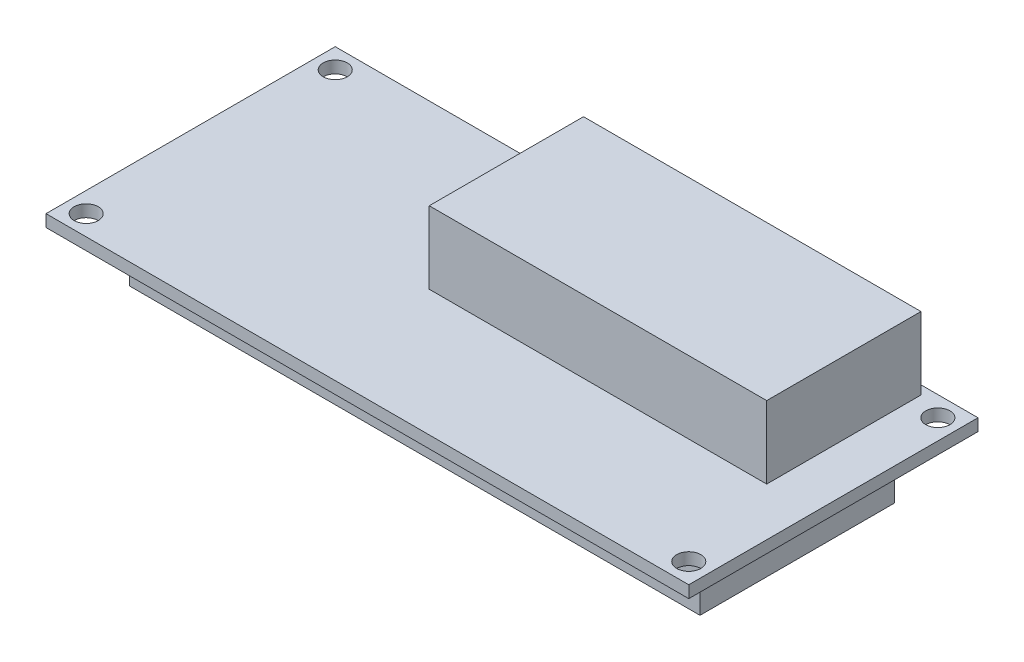
SolidWorks part; units mm, degrees
ref_plane "Спереди" through (0, 0, 0) normal (0, 0, 1) x (1, 0, 0)
ref_plane "Сверху" through (0, 0, 0) normal (0, 1, 0) x (1, 0, 0)
ref_plane "Справа" through (0, 0, 0) normal (1, 0, 0) x (0, 0, -1)
sketch "Эскиз1" plane through (0, 0, 0) normal (0, 1, 0) x (1, 0, 0)
  line L1 (-23.6364, 10.5455) -> (56.3636, 10.5455)
  line L2 (-23.6364, 10.5455) -> (-23.6364, -25.4545)
  line L3 (-23.6364, -25.4545) -> (56.3636, -25.4545)
  line L4 (56.3636, 10.5455) -> (56.3636, -25.4545)
  circle A0 centre (-21.1364, -22.9545) radius 1.5
  circle A1 centre (53.8636, 8.0455) radius 1.5
  circle A2 centre (-21.1364, 8.0455) radius 1.5
  circle A3 centre (53.8636, -22.9545) radius 1.5
  dimension "D1" = 80
  dimension "D2" = 36
  dimension "D3" = 2.5
  dimension "D4" = 2.5
  dimension "D5" = 2.5
  dimension "D6" = 2.5
  dimension "D7" = 2.5
  dimension "D8" = 2.5
  dimension "D9" = 2.5
  dimension "D10" = 2.5
extrude "Бобышка-Вытянуть1" add sketch "Эскиз1" along normal blind 1.5
sketch "Эскиз2" plane through (0, 0, 0) normal (0, -1, 0) x (1, 0, 0)
  line L0 (-23.6364, -10.5455) -> (-23.6364, 25.4545) construction
  line L1 (-19.1364, 19.5545) -> (51.8636, 19.5545)
  line L2 (-19.1364, 19.5545) -> (-19.1364, -4.6455)
  line L3 (-19.1364, -4.6455) -> (51.8636, -4.6455)
  line L4 (51.8636, 19.5545) -> (51.8636, -4.6455)
  line L5 (-23.6364, 25.4545) -> (56.3636, 25.4545) construction
  dimension "D1" = 71
  dimension "D2" = 24.2
  dimension "D3" = 4.5
  dimension "D4" = 5.9
extrude "Бобышка-Вытянуть2" add sketch "Эскиз2" along normal blind 7
sketch "Эскиз3" plane through (0, 1.5, 0) normal (0, 1, 0) x (1, 0, 0)
  line L0 (56.3636, -25.4545) -> (56.3636, 10.5455) construction
  line L1 (8.3636, 9.4455) -> (50.3636, 9.4455)
  line L2 (8.3636, 9.4455) -> (8.3636, -9.7545)
  line L3 (8.3636, -9.7545) -> (50.3636, -9.7545)
  line L4 (50.3636, 9.4455) -> (50.3636, -9.7545)
  line L5 (-23.6364, -25.4545) -> (56.3636, -25.4545) construction
  dimension "D1" = 42
  dimension "D2" = 19.2
  dimension "D3" = 6
  dimension "D4" = 15.7
extrude "Бобышка-Вытянуть3" add sketch "Эскиз3" along normal blind 9
sketch "Эскиз4" plane through (0, -7, 0) normal (0, -1, 0) x (1, 0, 0)
  line L0 (16.3636, 19.5545) -> (16.3636, -4.6455) construction
  line L1 (51.8636, 19.5545) -> (-19.1364, 19.5545) construction
  line L2 (-19.1364, -4.6455) -> (51.8636, -4.6455) construction
  line L3 (-19.1364, 7.4545) -> (51.8636, 7.4545) construction
  line L4 (-19.1364, 19.5545) -> (-19.1364, -4.6455) construction
  line L5 (51.8636, -4.6455) -> (51.8636, 19.5545) construction
  line L7 (-15.8364, 14.7045) -> (48.5636, 14.7045)
  line L8 (-15.8364, 14.7045) -> (-15.8364, 0.2045)
  line L9 (-15.8364, 0.2045) -> (48.5636, 0.2045)
  line L10 (48.5636, 14.7045) -> (48.5636, 0.2045)
  line L11 (-15.8364, 14.7045) -> (48.5636, 0.2045) construction
  line L12 (-15.8364, 0.2045) -> (48.5636, 14.7045) construction
  point P12 (16.3636, 7.4545)
  dimension "D1" = 64.4
  dimension "D2" = 14.5
extrude "Вырез-Вытянуть1" cut sketch "Эскиз4" against normal blind 0.1
equation "\"D5@Эскиз1\"=\"D4@Эскиз1\""
equation "\"D6@Эскиз1\"=\"D3@Эскиз1\""
equation "\"D7@Эскиз1\"=\"D3@Эскиз1\""
equation "\"D8@Эскиз1\"=\"D4@Эскиз1\""
equation "\"D9@Эскиз1\"=\"D4@Эскиз1\""
equation "\"D10@Эскиз1\"=\"D3@Эскиз1\""
